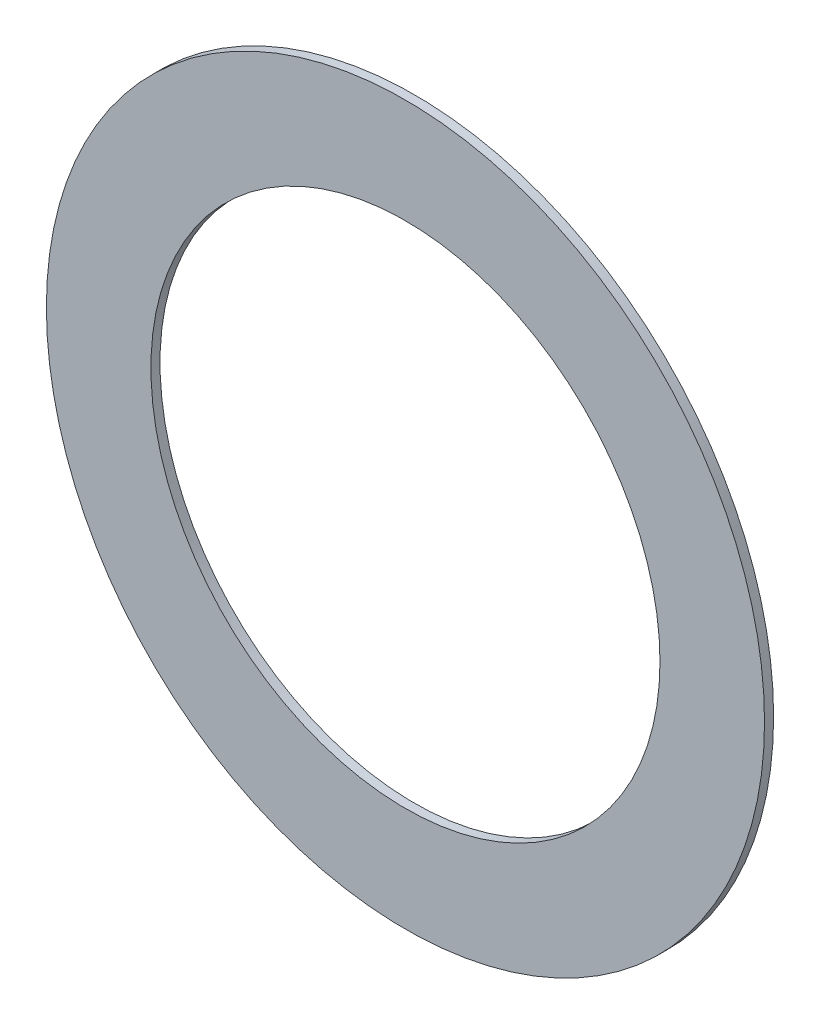
SolidWorks part; units mm, degrees
ref_plane "Plan1" through (0, 0, 0) normal (0, 0, 1) x (1, 0, 0)
ref_plane "Plan2" through (0, 0, 0) normal (0, 1, 0) x (1, 0, 0)
ref_plane "Plan3" through (0, 0, 0) normal (1, 0, 0) x (0, 0, -1)
sketch "Esquisse1" plane through (0, 0, 0) normal (0, 0, 1) x (1, 0, 0)
  circle A0 centre (0, 0) radius 19.75
  circle A1 centre (0, 0) radius 14
  dimension "D1" = 39.5
  dimension "D2" = 28
extrude "Base-Extrusion" add sketch "Esquisse1" along normal blind 0.5
